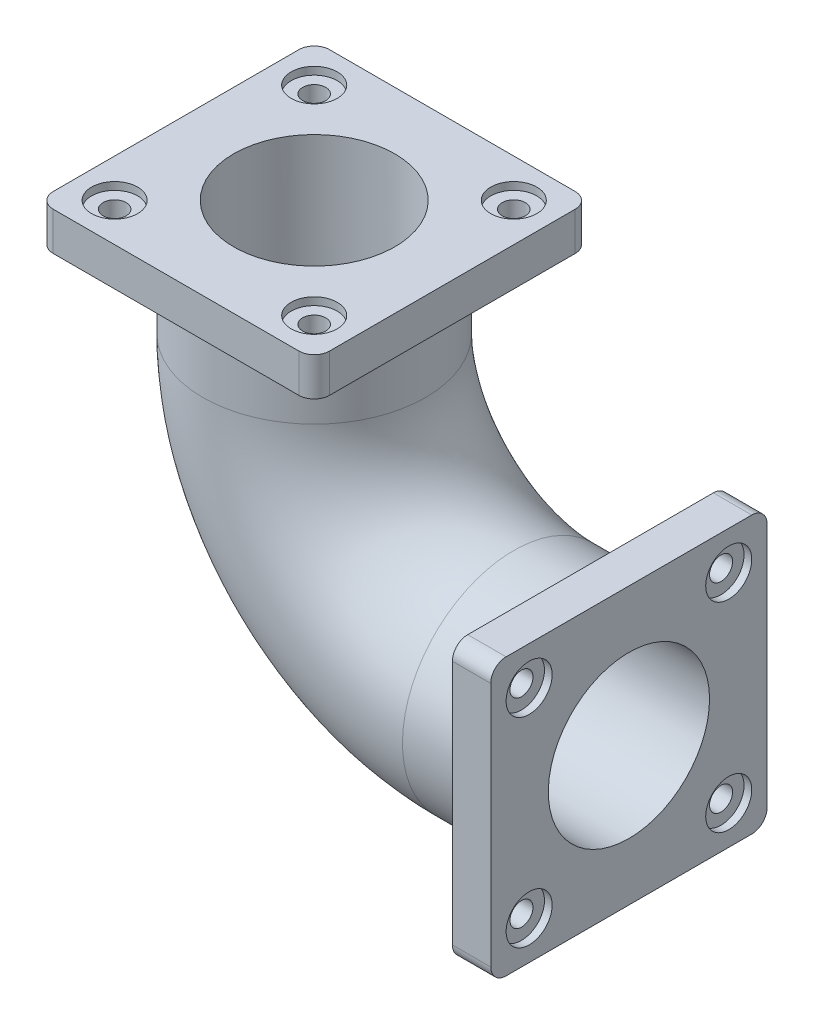
SolidWorks part; units mm, degrees
ref_plane "Front Plane" through (0, 0, 0) normal (0, 0, 1) x (1, 0, 0)
ref_plane "Top Plane" through (0, 0, 0) normal (0, 1, 0) x (1, 0, 0)
ref_plane "Right Plane" through (0, 0, 0) normal (1, 0, 0) x (0, 0, -1)
sketch "Sketch1" plane through (0, 0, 0) normal (0, 0, 1) x (1, 0, 0)
  line L0 (0, 0) -> (-150, 0)
  line L1 (-410, 260) -> (-410, 410)
  arc A0 (-150, 0) -> (-410, 260) centre (-150, 260) cw
  point P5 (0, 0)
  point P6 (0, 0)
  point P8 (0, 0)
  dimension "D2" = 260
  dimension "D1" = 150
sketch "Sketch2" plane through (0, 0, 0) normal (1, 0, 0) x (0, 0, -1)
  circle A0 centre (0, 0) radius 145
  dimension "D1" = 290
sweep "Sweep-Thin1" add profiles "Sketch2" path "Sketch1" parameters "D1"=40
sketch "Sketch3" plane through (0, 0, 0) normal (1, 0, 0) x (0, 0, -1)
  line L1 (-180, 180) -> (180, 180)
  line L2 (-180, 180) -> (-180, -180)
  line L3 (-180, -180) -> (180, -180)
  line L4 (180, 180) -> (180, -180)
  line L5 (-180, 180) -> (180, -180) construction
  line L6 (-180, -180) -> (180, 180) construction
  point P0 (0, 0)
  circle M3 centre (0, 0) radius 105
  circle M4 centre (0, 0) radius 145
  dimension "D1" = 360
  dimension "D2" = 360
extrude "Boss-Extrude1" add sketch "Sketch3" against normal blind 50 contours L4 L1 L2 L3 M4 | M4 M3
fillet "Fillet1" radius 20 4 edges at (-25, -180, 180) (-25, -180, -180) (-25, 180, -180) (-25, 180, 180)
sketch "Sketch6" plane through (0, 410, 0) normal (0, 1, 0) x (1, 0, 0)
  line L1 (-570, 180) -> (-250, 180)
  line L2 (-590, 160) -> (-590, -160)
  line L3 (-570, -180) -> (-250, -180)
  line L4 (-230, 160) -> (-230, -160)
  line L5 (-590, 180) -> (-230, -180) construction
  line L6 (-590, -180) -> (-230, 180) construction
  arc A0 (-250, 180) -> (-230, 160) centre (-250, 160) cw
  arc A1 (-590, -160) -> (-570, -180) centre (-570, -160) ccw
  arc A2 (-570, 180) -> (-590, 160) centre (-570, 160) ccw
  arc A3 (-250, -180) -> (-230, -160) centre (-250, -160) ccw
  point P0 (-410, 0)
  point P18 (0, 0)
  circle M9 centre (-410, 0) radius 105
  circle M10 centre (-410, 0) radius 145
  dimension "D3" = 20
  dimension "D1" = 360
  dimension "D2" = 360
extrude "Boss-Extrude2" add sketch "Sketch6" against normal blind 50 contours M10 M9 | L3 A3 L4 A0 L1 A2 L2 A1 M10
sketch "Sketch7" plane through (0, 0, 0) normal (1, 0, 0) x (0, 0, -1)
  line L1 (-130, 130) -> (130, 130) construction
  line L2 (-130, 130) -> (-130, -130) construction
  line L3 (-130, -130) -> (130, -130) construction
  line L4 (130, 130) -> (130, -130) construction
  line L5 (-130, 130) -> (130, -130) construction
  line L6 (-130, -130) -> (130, 130) construction
  circle A0 centre (-130, 130) radius 30
  point P0 (0, 0)
  dimension "D3" = 60
  dimension "D1" = 260
  dimension "D2" = 260
extrude "Cut-Extrude1" cut sketch "Sketch7" against normal blind 10
sketch "Sketch8" plane through (-10, 0, 0) normal (1, 0, 0) x (0, 0, -1)
  circle A0 centre (-130, 130) radius 15
  dimension "D1" = 30
extrude "Cut-Extrude2" cut sketch "Sketch8" against normal up to next
pattern_circular "CirPattern1" count 4 over 360 about axis through (0, 0, 0) along (1, 0, 0) of "Cut-Extrude2", "Cut-Extrude1"
sketch "Sketch9" plane through (0, 410, 0) normal (0, 1, 0) x (1, 0, 0)
  line L1 (-540, 130) -> (-280, 130) construction
  line L2 (-540, 130) -> (-540, -130) construction
  line L3 (-540, -130) -> (-280, -130) construction
  line L4 (-280, 130) -> (-280, -130) construction
  line L5 (-540, 130) -> (-280, -130) construction
  line L6 (-540, -130) -> (-280, 130) construction
  circle A0 centre (-540, 130) radius 30
  point P0 (-410, 0)
  dimension "D2" = 60
  dimension "D1" = 260
extrude "Cut-Extrude3" cut sketch "Sketch9" against normal blind 10
sketch "Sketch10" plane through (0, 400, 0) normal (0, 1, 0) x (1, 0, 0)
  circle A0 centre (-540, 130) radius 15
  dimension "D1" = 30
extrude "Cut-Extrude4" cut sketch "Sketch10" against normal up to next
pattern_circular "CirPattern2" count 4 over 360 about axis through (-410, 0, 0) along (0, 1, 0) of "Cut-Extrude4", "Cut-Extrude3"
